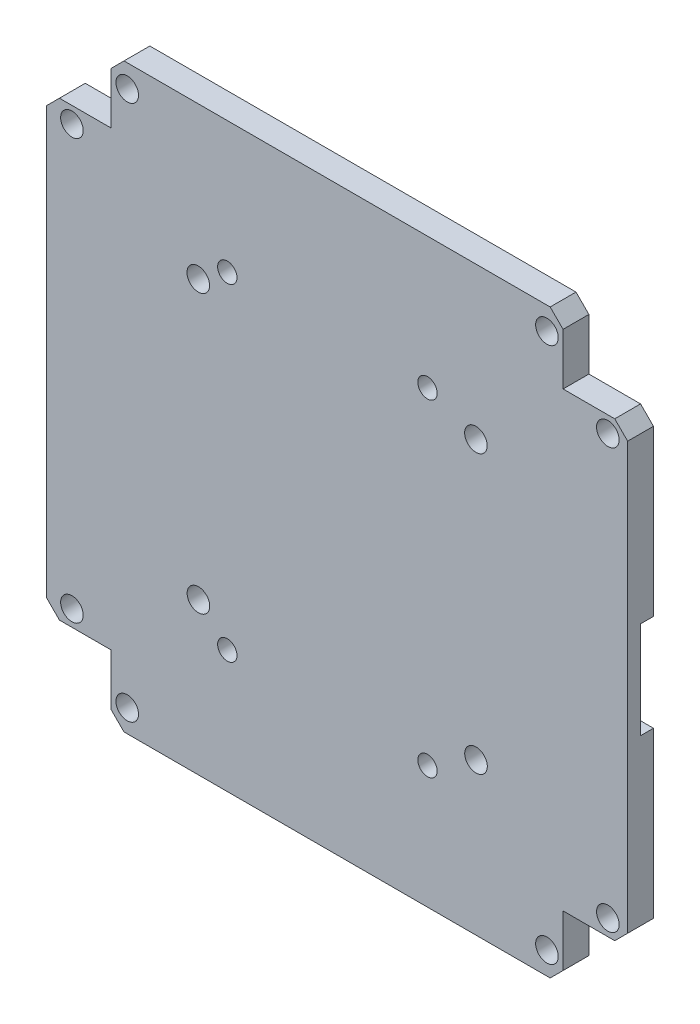
SolidWorks part; units mm, degrees
ref_plane "Plan de face" through (0, 0, 0) normal (0, 0, 1) x (1, 0, 0)
ref_plane "Plan de dessus" through (0, 0, 0) normal (0, 1, 0) x (1, 0, 0)
ref_plane "Plan de droite" through (0, 0, 0) normal (1, 0, 0) x (0, 0, -1)
sketch "Sketch1" plane through (0, 0, 0) normal (0, 0, 1) x (1, 0, 0)
  line L1 (-0.2317, 0.1934) -> (89.7683, 0.1934)
  line L2 (-0.2317, 0.1934) -> (-0.2317, 70.1934)
  line L3 (-0.2317, 70.1934) -> (89.7683, 70.1934)
  line L4 (89.7683, 0.1934) -> (89.7683, 70.1934)
  dimension "D1" = 70
  dimension "D2" = 90
extrude "Boss-Extrude1" add sketch "Sketch1" along normal blind 4
sketch "Sketch2" plane through (0, 0, 4) normal (0, 0, 1) x (1, 0, 0)
  line L0 (89.7683, 70.1934) -> (-0.2317, 70.1934) construction
  line L6 (-0.2317, 70.1934) -> (-0.2317, 0.1934) construction
  line L7 (89.7683, 0.1934) -> (89.7683, 70.1934) construction
  line L9 (-0.2317, 0.1934) -> (89.7683, 0.1934) construction
  circle A0 centre (3.7036, 2.6934) radius 1.75
  circle A1 centre (86.7036, 2.6944) radius 1.75
  circle A2 centre (86.7033, 67.6934) radius 1.75
  circle A3 centre (3.7033, 67.6934) radius 1.75
  circle A4 centre (23.2977, 13.6934) radius 1.75
  circle A5 centre (66.2841, 13.6934) radius 1.75
  circle A6 centre (66.2683, 56.6934) radius 1.75
  circle A7 centre (23.2683, 56.6934) radius 1.75
  dimension "D7" = 3.5
  dimension "D8" = 3.5
  dimension "D9" = 3.5
  dimension "D10" = 3.5
  dimension "D22" = 3.5
  dimension "D23" = 3.5
  dimension "D24" = 3.5
  dimension "D25" = 3.5
  dimension "D3" = 3.065
  dimension "D4" = 83
  dimension "D5" = 2.5
  dimension "D6" = 2.5
  dimension "D15" = 13.5
  dimension "D16" = 23.5295
  dimension "D17" = 13.5
  dimension "D18" = 13.5
  dimension "D19" = 23.5
  dimension "D20" = 13.5
  dimension "D21" = 23.5
extrude "Cut-Extrude1" cut sketch "Sketch2" against normal blind 5
chamfer "Chamfer1" distance 2 angle 45 1 edges at (89.7683, 0.1934, 2)
chamfer "Chamfer2" distance 2 angle 45 1 edges at (-0.2317, 0.1934, 2)
chamfer "Chamfer3" distance 2 angle 45 1 edges at (-0.2317, 70.1934, 2)
chamfer "Chamfer4" distance 2 angle 45 1 edges at (89.7683, 70.1934, 2)
sketch "Sketch4" plane through (0, 0.1934, 0) normal (0, -1, 0) x (-1, 0, 0)
  line L0 (-1.7683, 0) -> (-87.7683, 0) construction
  line L1 (-9.7683, -4) -> (-79.7683, -4)
  line L2 (-9.7683, -4) -> (-9.7683, 0)
  line L3 (-9.7683, 0) -> (-79.7683, 0)
  line L4 (-79.7683, -4) -> (-79.7683, 0)
  dimension "D1" = 70
  dimension "D2" = 8
  dimension "D3" = 4
  dimension "D4" = 0
sketch "Sketch5" plane through (0, 70.1934, 0) normal (0, 1, 0) x (1, 0, 0)
  line L0 (87.7683, 0) -> (1.7683, 0) construction
  line L1 (9.7683, -4) -> (79.7683, -4)
  line L2 (9.7683, -4) -> (9.7683, 0)
  line L3 (9.7683, 0) -> (79.7683, 0)
  line L4 (79.7683, -4) -> (79.7683, 0)
  dimension "D1" = 70
  dimension "D2" = 8
  dimension "D3" = 4
  dimension "D4" = 0
extrude "Boss-Extrude3" add sketch "Sketch5" along normal blind 10
extrude "Boss-Extrude4" add sketch "Sketch4" along normal blind 10
sketch "Sketch6" plane through (0, 0, 0) normal (0, 0, -1) x (-1, 0, 0)
  line L0 (-79.7683, 80.1934) -> (-79.7683, 70.1934) construction
  line L2 (-79.7683, -9.8066) -> (-79.7683, 0.1934) construction
  line L5 (-79.7683, 80.1934) -> (-9.7683, 80.1934) construction
  circle A0 centre (-12.2683, 76.6934) radius 1.75
  circle A1 centre (-77.2683, 76.6934) radius 1.75
  circle A2 centre (-77.2683, -6.3066) radius 1.75
  circle A3 centre (-12.2683, -6.3066) radius 1.75
  dimension "D7" = 3.5
  dimension "D8" = 3.5
  dimension "D9" = 3.5
  dimension "D10" = 3.5
  dimension "D1" = 83
  dimension "D2" = 83
  dimension "D3" = 65
  dimension "D4" = 65
  dimension "D5" = 2.5
  dimension "D6" = 2.5
  dimension "D11" = 3.5
  dimension "D12" = 3.5
extrude "Cut-Extrude2" cut sketch "Sketch6" against normal blind 10
chamfer "Chamfer5" distance 2 angle 45 4 edges at (9.7683, -9.8066, 2) (79.7683, -9.8066, 2) (9.7683, 80.1934, 2) (79.7683, 80.1934, 2)
sketch "Sketch7" plane through (0, 0, 0) normal (0, 0, -1) x (-1, 0, 0)
  line L0 (-24.7683, 55.1934) -> (-64.7683, 55.1934)
  line L1 (-64.7683, 55.1934) -> (-64.7683, 15.1934)
  line L2 (-64.7683, 15.1934) -> (-24.7683, 15.1934)
  line L3 (-24.7683, 15.1934) -> (-24.7683, 55.1934)
  line L4 (-77.7683, 80.1934) -> (-11.7683, 80.1934) construction
  line L5 (0.2317, 68.1934) -> (0.2317, 2.1934) construction
  dimension "D1" = 40
  dimension "D2" = 40
  dimension "D3" = 25
  dimension "D4" = 25
extrude "Cut-Extrude3" cut sketch "Sketch7" against normal blind 2
sketch "Sketch8" plane through (0, 0, 0) normal (0, 0, -1) x (-1, 0, 0)
  line L0 (-64.7683, 27.6934) -> (-89.7683, 27.6934)
  line L1 (-64.7683, 55.1934) -> (-64.7683, 15.1934) construction
  line L2 (-89.7683, 27.6934) -> (-89.7683, 42.6934)
  line L3 (-89.7683, 42.6934) -> (-64.7683, 42.6934)
  line L5 (-64.7683, 27.6934) -> (-64.7683, 42.6934)
  dimension "D1" = 15
  dimension "D2" = 25
  dimension "D3" = 12.5
extrude "Cut-Extrude4" cut sketch "Sketch8" against normal blind 2
sketch "Sketch9" plane through (0, 0, 0) normal (0, 0, -1) x (-1, 0, 0)
  circle A0 centre (-27.7683, 9.1934) radius 1.5
  circle A3 centre (-58.7683, 9.1934) radius 1.5
  circle A4 centre (-27.7683, 59.8563) radius 1.5
  circle A5 centre (-58.7683, 59.8563) radius 1.5
  dimension "D6" = 3
  dimension "D7" = 3
  dimension "D8" = 3
  dimension "D9" = 3
  dimension "D1" = 31
  dimension "D2" = 3
  dimension "D3" = 6
  dimension "D4" = 6
  dimension "D5" = 6
extrude "Cut-Extrude5" cut sketch "Sketch9" against normal blind 4
